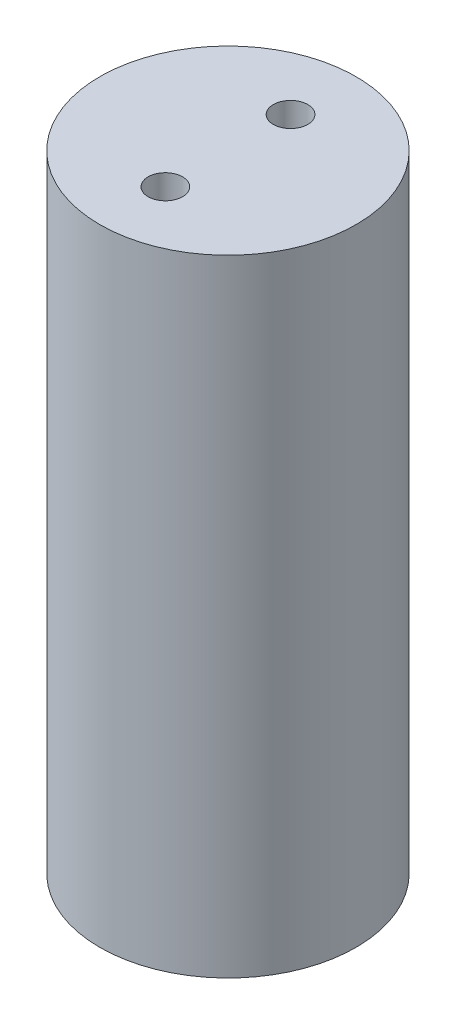
SolidWorks part; units mm, degrees
material "Rubber"
ref_plane "Front Plane" through (0, 0, 0) normal (0, 0, 1) x (1, 0, 0)
ref_plane "Top Plane" through (0, 0, 0) normal (0, 1, 0) x (1, 0, 0)
ref_plane "Right Plane" through (0, 0, 0) normal (1, 0, 0) x (0, 0, -1)
sketch "Sketch1" plane through (0, 0, 0) normal (0, 1, 0) x (1, 0, 0)
  circle A0 centre (0, 0) radius 2.6
extrude "Boss-Extrude1" add sketch "Sketch1" along normal mid plane 12.7
sketch "Sketch2" plane through (0, 0, 0) normal (0, 1, 0) x (1, 0, 0)
  circle A1 centre (0, -1.27) radius 0.35
  circle A2 centre (0, 1.27) radius 0.35
  dimension "D1" = 1.27
  dimension "D2" = 1.27
  dimension "D3" = 0.7
extrude "Cut-Extrude1" cut sketch "Sketch2" against normal mid plane 12.7
